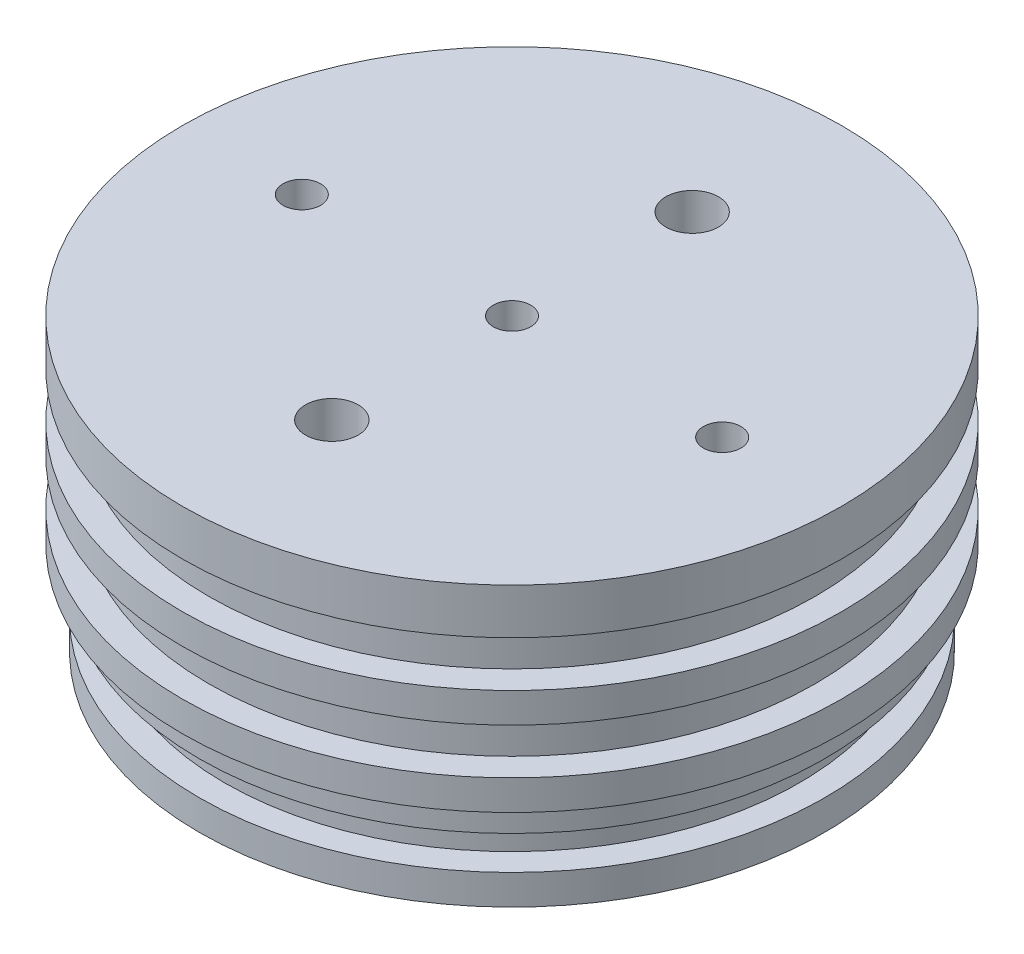
SolidWorks part; units mm, degrees
ref_plane "Front Plane" through (0, 0, 0) normal (0, 0, 1) x (1, 0, 0)
ref_plane "Top Plane" through (0, 0, 0) normal (0, 1, 0) x (1, 0, 0)
ref_plane "Right Plane" through (0, 0, 0) normal (1, 0, 0) x (0, 0, -1)
sketch "Sketch1" plane through (0, 0, 0) normal (0, 1, 0) x (1, 0, 0)
  circle A0 centre (0, 0) radius 69.723
  dimension "D1" = 139.446
extrude "Boss-Extrude1" add sketch "Sketch1" along normal blind 41.656
ref_plane "Plane1" through (69.723, 0, 0) normal (1, 0, 0) x (0, 0, -1)
sketch "Sketch3" plane through (0, 0, 0) normal (1, 0, 0) x (0, 0, -1)
  line L0 (69.723, 0) -> (69.723, 41.656) construction
  line L1 (69.723, 32.004) -> (64.135, 32.004)
  line L2 (69.723, 32.004) -> (69.723, 22.352)
  line L3 (69.723, 22.352) -> (64.135, 22.352)
  line L4 (64.135, 32.004) -> (64.135, 22.352)
  line L5 (-69.723, 0) -> (69.723, 0) construction
  line L6 (69.723, 16.002) -> (64.135, 16.002)
  line L7 (69.723, 16.002) -> (69.723, 6.35)
  line L8 (69.723, 6.35) -> (64.135, 6.35)
  line L9 (64.135, 16.002) -> (64.135, 6.35)
  dimension "D1" = 9.652
  dimension "D2" = 9.652
  dimension "D3" = 64.135
  dimension "D4" = 64.135
  dimension "D5" = 6.35
  dimension "D6" = 6.35
ref_axis "Axis1" through (0, 41.656, 0) along (0, -1, 0)
revolve "Cut-Revolve1" cut sketch "Sketch3" angle 360 about axis through (0, 41.656, 0) along (0, -1, 0)
sketch "Sketch4" plane through (0, 0, 0) normal (0, -1, 0) x (1, 0, 0)
  circle A0 centre (0, 0) radius 66.167
  dimension "D1" = 132.334
extrude "Boss-Extrude2" add sketch "Sketch4" along normal blind 19.8374
sketch "Sketch5" plane through (0, 0, 0) normal (1, 0, 0) x (0, 0, -1)
  line L0 (66.167, -19.8374) -> (66.167, 0) construction
  line L1 (66.167, -13.4874) -> (60.7695, -13.4874)
  line L2 (66.167, -13.4874) -> (66.167, -6.35)
  line L3 (66.167, -6.35) -> (60.7695, -6.35)
  line L4 (60.7695, -13.4874) -> (60.7695, -6.35)
  line L6 (-66.167, -19.8374) -> (66.167, -19.8374) construction
  dimension "D1" = 60.7695
  dimension "D2" = 7.1374
  dimension "D3" = 6.35
revolve "Cut-Revolve2" cut sketch "Sketch5" angle 360 about axis through (0, 41.656, 0) along (0, -1, 0)
sketch "Sketch7" plane through (0, -19.8374, 0) normal (0, -1, 0) x (1, 0, 0)
  circle A0 centre (0, 0) radius 24.765
  dimension "D1" = 49.53
extrude "Cut-Extrude1" [suppressed] cut sketch "Sketch7" against normal blind 38.1 contours A0
sketch "Sketch8" plane through (0, 41.656, 0) normal (0, 1, 0) x (1, 0, 0)
  line L0 (0, 0) -> (0, 38.1) construction
  line L1 (0, -33.8214) -> (0, 33.8214) construction
  dimension "D1" = 38.1
hole_wizard "Pipe Tap Drill for 1/4 Tap1" positions "3DSketch1" profile "Sketch9" hole size "1/4" standard "ANSI Inch" end condition up to next
sketch3d "3DSketch1"
  point P0 (0, 41.656, -38.1)
sketch "Sketch9" plane through (0, 41.656, -38.1) normal (1, 0, 0) x (0, 0, 1)
  line L0 (0, 0) -> (0, 61.4934)
  line L1 (0, 61.4934) -> (5.5626, 61.4934)
  line L2 (5.5626, 61.4934) -> (5.5626, 0)
  line L5 (5.5626, 0) -> (0, 0)
  line L11 (0, -6.35) -> (0, 107.95) construction
  dimension "Thru Hole Dia." = 11.1252
  dimension "Thru Hole Depth" = 61.4934
mirror "Mirror1" about plane through (0, 0, 0) normal (0, 0, 1) of "Pipe Tap Drill for 1/4 Tap1"
sketch "Sketch13" plane through (0, 41.656, 0) normal (0, 1, 0) x (1, 0, 0)
  point P0 (0, 0)
hole_wizard "Tap Drill for 3/8-16 Tap1" positions "3DSketch4" profile "Sketch16" hole size "3/8-16" standard "ANSI Inch"
sketch3d "3DSketch4"
  point P0 (0, 41.656, 0)
sketch "Sketch16" plane through (0, 41.656, 0) normal (1, 0, 0) x (0, 0, 1)
  line L0 (0, 0) -> (0, 27.7847)
  line L1 (0, 27.7847) -> (3.9687, 25.4)
  line L2 (3.9687, 25.4) -> (3.9687, 0)
  line L5 (3.9687, 0) -> (0, 0)
  line L10 (0, 27.7847) -> (-3.9688, 25.4) construction
  line L11 (0, -6.35) -> (0, 107.95) construction
  dimension "Hole Dia." = 7.9375
  dimension "Hole Depth" = 25.4
  dimension "Drill Angle" = 118
sketch "Sketch21" plane through (0, 41.656, 0) normal (0, 1, 0) x (1, 0, 0)
  point P0 (0, 38.1)
  point P1 (0, -38.1)
hole_wizard "Pipe Tap Drill for 1/4 Tap2" positions "3DSketch9" profile "Sketch23" hole size "1/4" standard "ANSI Inch" end condition up to next
sketch3d "3DSketch9"
  point P0 (0, 41.656, 38.1)
  point P3 (0, 41.656, -38.1)
sketch "Sketch23" plane through (0, 41.656, 38.1) normal (1, 0, 0) x (0, 0, 1)
  line L0 (0, 0) -> (0, 61.4934)
  line L1 (0, 61.4934) -> (5.5626, 61.4934)
  line L2 (5.5626, 61.4934) -> (5.5626, 0)
  line L5 (5.5626, 0) -> (0, 0)
  line L11 (0, -6.35) -> (0, 107.95) construction
  dimension "Thru Hole Dia." = 11.1252
  dimension "Thru Hole Depth" = 61.4934
sketch "snap ring groove" [suppressed] plane through (0, 0, 0) normal (0, 0, 1) x (1, 0, 0)
  line L2 (-66.167, -19.8374) -> (66.167, -19.8374) construction
  line L3 (-24.765, -16.6624) -> (-26.9494, -16.6624)
  line L4 (-24.765, -16.6624) -> (-24.765, -14.8844)
  line L5 (-24.765, -14.8844) -> (-26.9494, -14.8844)
  line L6 (-26.9494, -16.6624) -> (-26.9494, -14.8844)
  line L7 (-24.765, 18.2626) -> (-24.765, -19.8374) construction
  point P9 (-26.9494, -15.7734)
  dimension "D1" = 1.778
  dimension "D2" = 26.9494
  dimension "D3" = 3.175
revolve "Cut-Revolve3" [suppressed] cut sketch "snap ring groove" angle 360 about axis through (0, 41.656, 0) along (0, -1, 0)
sketch "Sketch24" plane through (0, 41.656, 0) normal (0, 1, 0) x (1, 0, 0)
  line L0 (-33.8214, 0) -> (33.8214, 0) construction
  point P0 (-44.45, 0)
  point P1 (44.45, 0)
  dimension "D1" = 44.45
  dimension "D2" = 44.45
hole_wizard "Tap Drill for 3/8-16 Tap2" positions "3DSketch11" profile "Sketch26" hole size "3/8-16" standard "ANSI Inch"
sketch3d "3DSketch11"
  point P0 (-44.45, 41.656, 0)
  point P3 (44.45, 41.656, 0)
sketch "Sketch26" plane through (-44.45, 41.656, 0) normal (1, 0, 0) x (0, 0, 1)
  line L0 (0, 0) -> (0, 21.4347)
  line L1 (0, 21.4347) -> (3.9687, 19.05)
  line L2 (3.9687, 19.05) -> (3.9687, 0)
  line L5 (3.9687, 0) -> (0, 0)
  line L10 (0, 21.4347) -> (-3.9688, 19.05) construction
  line L11 (0, -6.35) -> (0, 107.95) construction
  dimension "Hole Dia." = 7.9375
  dimension "Hole Depth" = 19.05
  dimension "Drill Angle" = 118
